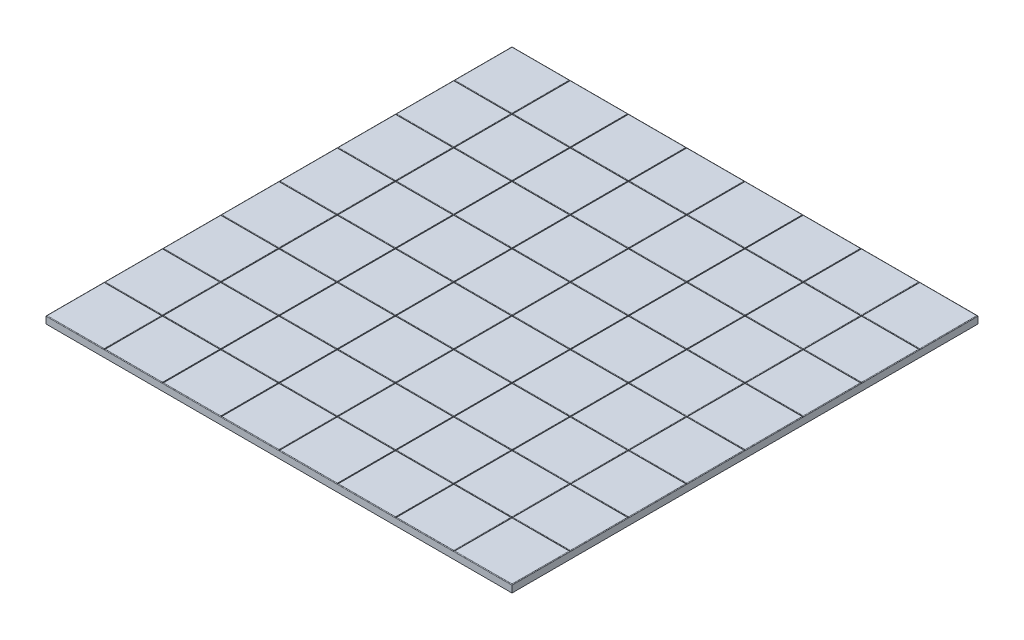
SolidWorks part; units mm, degrees
ref_plane "Front Plane" through (0, 0, 0) normal (0, 0, 1) x (1, 0, 0)
ref_plane "Top Plane" through (0, 0, 0) normal (0, 1, 0) x (1, 0, 0)
ref_plane "Right Plane" through (0, 0, 0) normal (1, 0, 0) x (0, 0, -1)
sketch "Sketch2" plane through (0, 0, 0) normal (0, 1, 0) x (1, 0, 0)
  line L1 (-1166.1316, -628.3949) -> (433.8684, -628.3949)
  line L2 (-1166.1316, -628.3949) -> (-1166.1316, 971.6051)
  line L3 (-1166.1316, 971.6051) -> (433.8684, 971.6051)
  line L4 (433.8684, -628.3949) -> (433.8684, 971.6051)
extrude "Boss-Extrude1" add sketch "Sketch2" against normal blind 25
ref_plane "Plane1" through (0, 0, 750) normal (0, 0, 1) x (1, 0, 0)
sketch "Sketch4" plane through (0, 0, 750) normal (0, 0, 1) x (1, 0, 0)
  line L3 (-1166.1316, 0) -> (433.8684, 0) construction
  line L6 (-1164.1316, 0) -> (-1166.1316, 0)
  line L7 (-1166.1316, 0) -> (-1166.1316, -2)
  arc A0 (-1164.1316, 0) -> (-1166.1316, -2) centre (-1164.1316, -2) ccw
  point P12 (-1166.1316, 0)
  dimension "D1" = 2
extrude "Cut-Extrude1" cut sketch "Sketch4" against normal blind 1800 contours L6 L7 A0
sketch "Sketch5" plane through (0, 0, 750) normal (0, 0, 1) x (1, 0, 0)
  line L0 (-1166.1316, 0.0028) -> (-1164.1298, 0.0028)
  line L1 (-1166.1316, -25) -> (-1166.1316, -2) construction
  line L2 (-968.2443, 0.0046) -> (-964.2443, 0.0046)
  line L3 (-1166.1316, -21.7818) -> (-1166.1316, -1.9972)
  line L4 (-568.0944, 0.0247) -> (-564.0944, 0.0247)
  line L5 (-768.2107, 0.0335) -> (-764.2107, 0.0335)
  line L6 (31.9678, 0.0183) -> (35.8674, 0.0183)
  line L8 (-368.1725, 0.007) -> (-364.1725, 0.007)
  line L9 (-167.9842, 0.0514) -> (-163.9842, 0.0514)
  line L10 (-1166.1316, -1.9972) -> (-1166.1316, 0.0028)
  line L11 (431.8684, 0) -> (433.8684, 0)
  line L12 (433.8684, -25) -> (433.8684, 0) construction
  line L15 (-1164.1316, 0) -> (433.8684, 0) construction
  line L16 (231.8684, 0) -> (235.8684, 0)
  arc A0 (433.8684, -2) -> (431.8684, 0) centre (431.8684, -2) ccw
  arc A1 (233.8684, -2) -> (231.8684, 0) centre (231.8684, -2) ccw
  arc A2 (233.8684, -2) -> (235.8684, 0) centre (235.8684, -2) cw
  arc A3 (33.9176, -1.981) -> (31.9678, 0.0183) centre (31.9176, -1.981) ccw
  arc A4 (33.9176, -1.981) -> (35.8674, 0.0183) centre (35.9176, -1.981) cw
  arc A5 (-366.1725, -1.993) -> (-368.1725, 0.007) centre (-368.1725, -1.993) ccw
  arc A6 (-366.1725, -1.993) -> (-364.1725, 0.007) centre (-364.1725, -1.993) cw
  arc A7 (-165.9842, -1.9486) -> (-167.9842, 0.0514) centre (-167.9842, -1.9486) ccw
  arc A8 (-165.9842, -1.9486) -> (-163.9842, 0.0514) centre (-163.9842, -1.9486) cw
  arc A9 (-1166.1316, -1.9972) -> (-1164.1298, 0.0028) centre (-1164.1316, -1.9972) cw
  arc A11 (-566.0944, -1.9753) -> (-568.0944, 0.0247) centre (-568.0944, -1.9753) ccw
  arc A12 (-566.0944, -1.9753) -> (-564.0944, 0.0247) centre (-564.0944, -1.9753) cw
  arc A15 (-766.2107, -1.9665) -> (-768.2107, 0.0335) centre (-768.2107, -1.9665) ccw
  arc A16 (-766.2107, -1.9665) -> (-764.2107, 0.0335) centre (-764.2107, -1.9665) cw
  arc A19 (-966.2443, -1.9954) -> (-968.2443, 0.0046) centre (-968.2443, -1.9954) ccw
  arc A20 (-966.2443, -1.9954) -> (-964.2443, 0.0046) centre (-964.2443, -1.9954) cw
  point P21 (433.8684, 0)
  point P28 (233.8684, 0)
  point P34 (33.9678, 0.0183)
  point P41 (33.8127, -6.7131)
  point P42 (-366.1725, 0.007)
  point P48 (-165.9842, 0.0514)
  point P63 (-566.0944, 0.0247)
  point P77 (-766.2107, 0.0335)
  point P91 (-966.2443, 0.0046)
  dimension "D1" = 2
  dimension "D2" = 2
  dimension "D3" = 2
  dimension "D4" = 2
  dimension "D5" = 2
  dimension "D6" = 2
  dimension "D7" = 2
  dimension "D9" = 2
  dimension "D11" = 2
extrude "Cut-Extrude5" cut sketch "Sketch5" against normal blind 1800 contours A19 A20 L2 | A15 A16 L5 | A11 A12 L4 | A5 A6 L8 | A7 A8 L9 | A3 A4 L6 | A1 A2 L16
sketch "Sketch8" plane through (0, 0, 628.3949) normal (0, 0, 1) x (1, 0, 0)
  line L0 (431.8684, 0) -> (433.8684, 0)
  line L1 (433.8684, 0) -> (433.8684, -2)
  arc A0 (433.8684, -2) -> (431.8684, 0) centre (431.8684, -2) ccw
  point P9 (433.8684, 0)
  dimension "D1" = 2
extrude "Cut-Extrude6" cut sketch "Sketch8" against normal blind 1800 contours L1 A0 L0
ref_plane "Plane3" through (550, 0, 0) normal (1, 0, 0) x (0, 0, -1)
sketch "Sketch13" plane through (550, 0, 0) normal (1, 0, 0) x (0, 0, -1)
  line L0 (969.6051, 0) -> (971.6051, 0)
  line L1 (-628.3949, 0) -> (-628.3949, -2)
  line L4 (971.6051, 0) -> (971.6051, -2)
  line L6 (-626.3949, 0) -> (-628.3949, 0)
  arc A0 (-626.3949, 0) -> (-628.3949, -2) centre (-626.3949, -2) ccw
  arc A1 (971.6051, -2) -> (969.6051, 0) centre (969.6051, -2) ccw
  point P10 (-628.3949, 0)
  point P15 (971.6051, 0)
  dimension "D1" = 2
  dimension "D2" = 2
extrude "Cut-Extrude9" cut sketch "Sketch13" against normal blind 1800
sketch "Sketch14" plane through (433.8684, 0, 0) normal (1, 0, 0) x (0, 0, -1)
  line L0 (-628.3949, -25) -> (-428.3949, -25)
  line L1 (-628.3949, -25) -> (971.6051, -25) construction
  line L2 (-430.3949, 0) -> (-426.3949, 0)
  arc A0 (-428.3949, -2) -> (-430.3949, 0) centre (-430.3949, -2) ccw
  arc A1 (-428.3949, -2) -> (-426.3949, 0) centre (-426.3949, -2) cw
  dimension "D1" = 2
  dimension "D2" = 2
extrude "Cut-Extrude10" cut sketch "Sketch14" against normal blind 1800 contours A0 A1 L2
sketch "Sketch15" plane through (550, 0, 0) normal (1, 0, 0) x (0, 0, -1)
  line L0 (-428.3949, -2) -> (-228.3949, -2)
  line L1 (971.6051, -2) -> (-428.3949, -2) construction
  line L2 (-30.3949, 0) -> (-26.3949, 0)
  line L3 (-230.3949, 0) -> (-226.3949, 0)
  line L4 (969.6051, 0) -> (-426.3949, 0) construction
  arc A0 (-228.3949, -2) -> (-230.3949, 0) centre (-230.3949, -2) ccw
  arc A1 (-226.3949, 0) -> (-228.3949, -2) centre (-226.3949, -2) ccw
  arc A2 (-28.3949, -2) -> (-30.3949, 0) centre (-30.3949, -2) ccw
  arc A3 (-26.3949, 0) -> (-28.3949, -2) centre (-26.3949, -2) ccw
  point P17 (-228.3949, 0)
  point P23 (-28.3949, 0)
  dimension "D1" = 2
  dimension "D2" = 2
  dimension "D3" = 2
  dimension "D4" = 2
extrude "Cut-Extrude11" cut sketch "Sketch15" against normal blind 1800 contours A3 L2 A2 | A1 L3 A0
sketch "Sketch16" plane through (550, 0, 0) normal (1, 0, 0) x (0, 0, -1)
  line L0 (169.6051, 0) -> (173.6051, 0)
  line L1 (971.6051, -2) -> (-28.3949, -2) construction
  line L4 (571.6051, -2) -> (771.6051, -2)
  line L5 (771.6051, -2) -> (971.6051, -2)
  line L6 (369.6051, 0) -> (373.6051, 0)
  line L7 (969.6051, 0) -> (-26.3949, 0) construction
  arc A0 (171.6051, -2) -> (169.6051, 0) centre (169.6051, -2) ccw
  arc A1 (173.6051, 0) -> (171.6051, -2) centre (173.6051, -2) ccw
  arc A2 (371.6051, -2) -> (369.6051, 0) centre (369.6051, -2) ccw
  arc A3 (373.6051, 0) -> (371.6051, -2) centre (373.6051, -2) ccw
  arc A4 (571.6051, -2) -> (569.6051, 0) centre (569.6051, -2) ccw
  arc A5 (573.6051, 0) -> (571.6051, -2) centre (573.6051, -2) ccw
  point P20 (171.6051, 0)
  point P25 (371.6051, 0)
  point P30 (571.6051, 0)
  dimension "D1" = 2
  dimension "D2" = 2
  dimension "D3" = 2
  dimension "D4" = 2
  dimension "D5" = 2
  dimension "D6" = 2
extrude "Cut-Extrude12" cut sketch "Sketch16" against normal blind 1800 contours A1 L0 A0 | A3 L6 A2
sketch "Sketch17" plane through (550, 0, 0) normal (1, 0, 0) x (0, 0, -1)
  line L0 (569.6051, 0) -> (573.6051, 0)
  line L1 (971.6051, -2) -> (371.6051, -2) construction
  line L2 (769.6051, 0) -> (773.6051, 0)
  line L4 (969.6051, 0) -> (373.6051, 0) construction
  arc A0 (571.6051, -2) -> (569.6051, 0) centre (569.6051, -2) ccw
  arc A1 (573.6051, 0) -> (571.6051, -2) centre (573.6051, -2) ccw
  arc A2 (771.6051, -2) -> (769.6051, 0) centre (769.6051, -2) ccw
  arc A3 (773.6051, 0) -> (771.6051, -2) centre (773.6051, -2) ccw
  point P17 (571.6051, 0)
  point P22 (771.6051, 0)
  dimension "D1" = 2
  dimension "D2" = 2
  dimension "D3" = 2
  dimension "D4" = 2
extrude "Cut-Extrude13" cut sketch "Sketch17" against normal blind 1800 contours L2 A3 A2 | L0 A1 A0
ref_plane "Plane4" through (0, 0, 0) normal (0, 1, 0) x (1, 0, 0)
sketch "Sketch18" plane through (0, 0, 0) normal (0, 1, 0) x (1, 0, 0)
  circle A0 centre (335.8684, -530.3949) radius 25
  circle A1 centre (135.8684, -530.3949) radius 25
  circle A2 centre (-64.1316, -530.3949) radius 25
  circle A3 centre (-264.1316, -530.3949) radius 25
  circle A4 centre (-464.1316, -530.3949) radius 25
  circle A5 centre (-664.1316, -530.3949) radius 25
  circle A6 centre (-864.1316, -530.3949) radius 25
  circle A7 centre (-1064.1316, -530.3949) radius 25
  circle A8 centre (135.8684, -330.3949) radius 25
  circle A9 centre (-64.1316, -330.3949) radius 25
  circle A10 centre (-264.1316, -330.3949) radius 25
  circle A11 centre (-464.1316, -330.3949) radius 25
  circle A12 centre (-664.1316, -330.3949) radius 25
  circle A13 centre (-864.1316, -330.3949) radius 25
  circle A14 centre (-1064.1316, -330.3949) radius 25
  circle A43 centre (135.8684, 669.6051) radius 25
  circle A44 centre (-64.1316, 669.6051) radius 25
  circle A45 centre (-264.1316, 669.6051) radius 25
  circle A46 centre (-464.1316, 669.6051) radius 25
  circle A47 centre (-664.1316, 669.6051) radius 25
  circle A48 centre (-864.1316, 669.6051) radius 25
  circle A49 centre (-1064.1316, 669.6051) radius 25
  circle A50 centre (135.8684, 869.6051) radius 25
  circle A51 centre (-64.1316, 869.6051) radius 25
  circle A52 centre (-264.1316, 869.6051) radius 25
  circle A53 centre (-464.1316, 869.6051) radius 25
  circle A54 centre (-664.1316, 869.6051) radius 25
  circle A55 centre (-864.1316, 869.6051) radius 25
  circle A56 centre (-1064.1316, 869.6051) radius 25
  circle A57 centre (335.8684, -330.3949) radius 25
  circle A62 centre (335.8684, 669.6051) radius 25
  circle A63 centre (335.8684, 869.6051) radius 25
  circle A64 centre (335.8684, 269.6051) radius 25
  circle A65 centre (135.8684, 269.6051) radius 25
  circle A66 centre (-64.1316, 269.6051) radius 25
  circle A67 centre (-264.1316, 269.6051) radius 25
  circle A68 centre (-464.1316, 269.6051) radius 25
  circle A69 centre (-664.1316, 269.6051) radius 25
  circle A70 centre (135.8684, -130.3949) radius 25
  circle A71 centre (-64.1316, -130.3949) radius 25
  circle A72 centre (-264.1316, -130.3949) radius 25
  circle A73 centre (-464.1316, -130.3949) radius 25
  circle A74 centre (-664.1316, -130.3949) radius 25
  circle A75 centre (-864.1316, -130.3949) radius 25
  circle A76 centre (-1064.1316, -130.3949) radius 25
  circle A77 centre (135.8684, 69.6051) radius 25
  circle A78 centre (-64.1316, 69.6051) radius 25
  circle A79 centre (-264.1316, 69.6051) radius 25
  circle A80 centre (-464.1316, 69.6051) radius 25
  circle A81 centre (-664.1316, 69.6051) radius 25
  circle A82 centre (-864.1316, 69.6051) radius 25
  circle A83 centre (-1064.1316, 69.6051) radius 25
  circle A84 centre (-864.1316, 269.6051) radius 25
  circle A85 centre (-1064.1316, 269.6051) radius 25
  circle A86 centre (135.8684, 469.6051) radius 25
  circle A87 centre (-64.1316, 469.6051) radius 25
  circle A88 centre (-264.1316, 469.6051) radius 25
  circle A89 centre (-464.1316, 469.6051) radius 25
  circle A90 centre (-664.1316, 469.6051) radius 25
  circle A91 centre (-864.1316, 469.6051) radius 25
  circle A92 centre (-1064.1316, 469.6051) radius 25
  circle A93 centre (335.8684, -130.3949) radius 25
  circle A94 centre (335.8684, 69.6051) radius 25
  circle A95 centre (335.8684, 469.6051) radius 25
  dimension "D1" = 50
  dimension "D2" = 8
  dimension "D3" = 8
